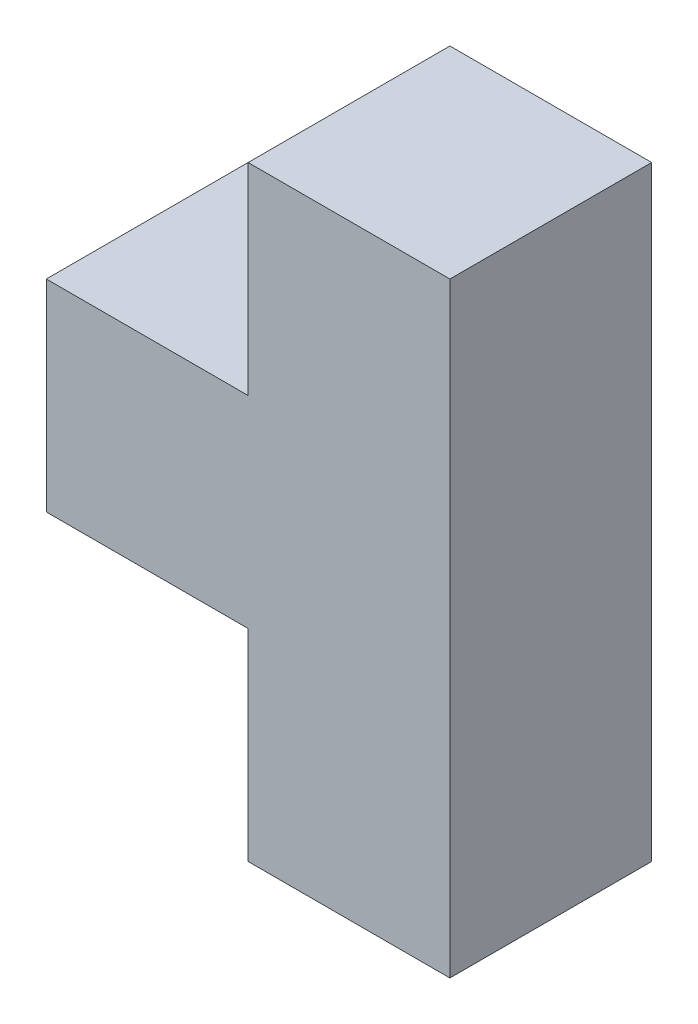
SolidWorks part; units mm, degrees
ref_plane "Front Plane" through (0, 0, 0) normal (1, 0, 0) x (0, 1, 0)
ref_plane "Top Plane" through (0, 0, 0) normal (0, 0, 1) x (0, 1, 0)
ref_plane "Right Plane" through (0, 0, 0) normal (0, 1, 0) x (-1, 0, 0)
sketch "Sketch1" plane through (0, 0, 0) normal (0, 0, 1) x (0, 1, 0)
  line L1 (-45, -30) -> (45, -30)
  line L2 (-45, -30) -> (-45, 30)
  line L3 (-45, 30) -> (45, 30)
  line L4 (45, -30) -> (45, 30)
  line L5 (-45, -30) -> (45, 30) construction
  line L6 (-45, 30) -> (45, -30) construction
  point P0 (0, 0)
  dimension "D1" = 90
  dimension "D2" = 60
extrude "Boss-Extrude1" add sketch "Sketch1" along normal mid plane 30
sketch "Sketch2" plane through (0, 0, 15) normal (0, 0, 1) x (1, 0, 0)
  line L0 (0, 45) -> (0, 15)
  line L1 (30, 45) -> (-30, 45) construction
  line L2 (0, 15) -> (-30, 15)
  line L3 (-30, 45) -> (-30, -45) construction
  line L4 (0, -45) -> (0, -15)
  line L5 (-30, -45) -> (30, -45) construction
  line L6 (0, -15) -> (-30, -15)
  line M3 (30, 45) -> (-30, 45)
  line M4 (-30, 45) -> (-30, -45)
  line M5 (-30, -45) -> (30, -45)
  dimension "D1" = 30
  dimension "D2" = 30
extrude "Cut-Extrude1" cut sketch "Sketch2" against normal through all contours L4 L6 M4 M5 | L2 L0 M3 M4
